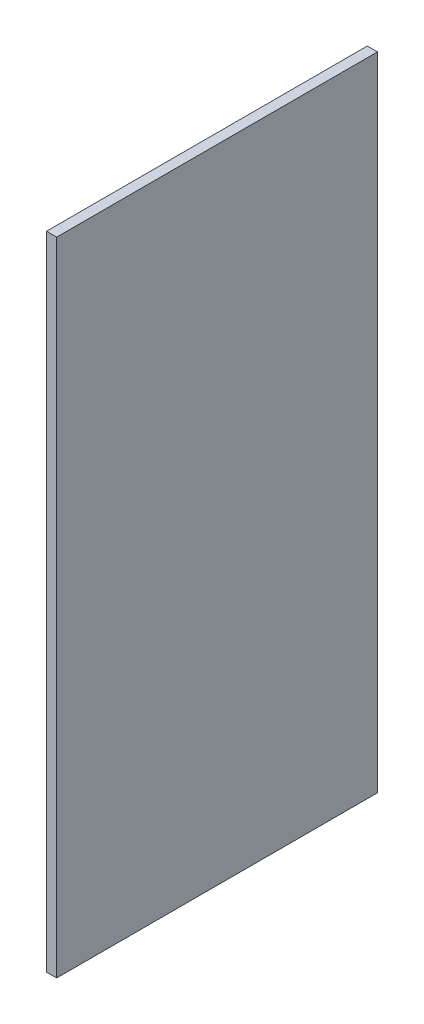
SolidWorks part; units mm, degrees
material "Oak"
ref_plane "Front Plane" through (0, 0, 0) normal (0, 0, 1) x (1, 0, 0)
ref_plane "Top Plane" through (0, 0, 0) normal (0, 1, 0) x (1, 0, 0)
ref_plane "Right Plane" through (0, 0, 0) normal (1, 0, 0) x (0, 0, -1)
sketch "Sketch1" plane through (0, 0, 0) normal (1, 0, 0) x (0, 0, -1)
  line L1 (0, 0) -> (100, 0)
  line L2 (0, 0) -> (0, -200)
  line L3 (0, -200) -> (100, -200)
  line L4 (100, 0) -> (100, -200)
  dimension "D1" = 100
  dimension "D2" = 200
extrude "Boss-Extrude1" add sketch "Sketch1" along normal blind 3.175
